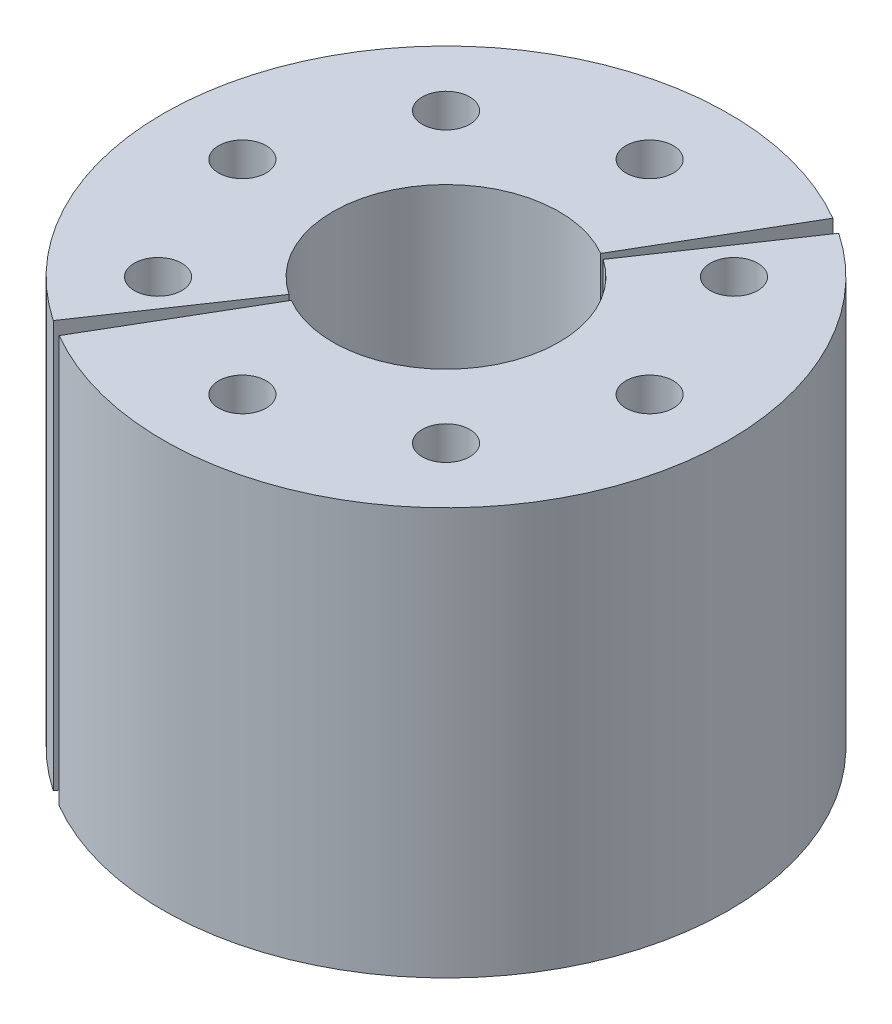
SolidWorks part; units mm, degrees
ref_plane "Спереди" through (0, 0, 0) normal (0, 0, 1) x (1, 0, 0)
ref_plane "Сверху" through (0, 0, 0) normal (0, 1, 0) x (1, 0, 0)
ref_plane "Справа" through (0, 0, 0) normal (1, 0, 0) x (0, 0, -1)
sketch "Эскиз1" plane through (0, 0, 0) normal (0, 1, 0) x (1, 0, 0)
  line L1 (-5.6063, -8.2806) -> (-14.0159, -20.7016)
  line L3 (-5.0408, -8.6366) -> (-12.602, -21.5914)
  line L4 (5.0408, 8.6366) -> (12.602, 21.5914)
  line L5 (5.6063, 8.2806) -> (14.0159, 20.7016)
  circle A0 centre (0, 0) radius 10
  circle A1 centre (0, 0) radius 25
  circle A3 centre (-18, 0) radius 2.1
  circle A4 centre (-12.7279, 12.7279) radius 2.1
  circle A5 centre (0, 18) radius 2.1
  circle A6 centre (12.7279, 12.7279) radius 2.1
  circle A7 centre (18, 0) radius 2.1
  circle A8 centre (12.7279, -12.7279) radius 2.1
  circle A9 centre (0, -18) radius 2.1
  circle A10 centre (-12.7279, -12.7279) radius 2.1
extrude "Бобышка-Вытянуть1" add sketch "Эскиз1" along normal blind 36 contours L4 A1 L1 A0 A10 A5 A4 A3 | L3 A1 L5 A0 A9 A8 A7 A6
